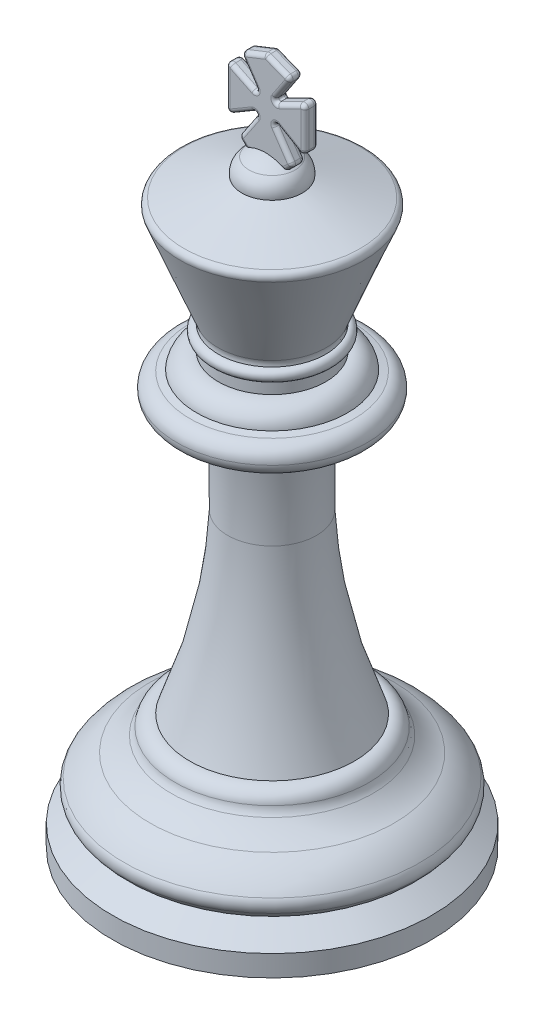
SolidWorks part; units mm, degrees
material "CA"
ref_plane "Front Plane" through (0, 0, 0) normal (0, 0, 1) x (1, 0, 0)
ref_plane "Top Plane" through (0, 0, 0) normal (0, 1, 0) x (1, 0, 0)
ref_plane "Right Plane" through (0, 0, 0) normal (1, 0, 0) x (0, 0, -1)
sketch "Sketch1" plane through (0, 0, 0) normal (0, 0, 1) x (1, 0, 0)
  line L0 (15.1895, 237.7707) -> (158.4441, 242.5229) construction
  line L1 (0, 0) -> (0, 46.3984)
  line L3 (-12.2343, 0) -> (0, 0)
  line L4 (-12.2343, 0) -> (-12.2343, 1.6147)
  line L5 (-12.2343, 1.6147) -> (-10.4135, 2.8152)
  line L6 (-6.3061, 29.5191) -> (-3.8024, 29.5191)
  line L7 (-6.3061, 31.6075) -> (-5.7756, 31.7201)
  line L8 (-4.1176, 32.9569) -> (-4.1176, 33.9091)
  line L9 (-4.157, 35.2434) -> (-7.0464, 42.4789)
  line L10 (-6.7515, 43.1108) -> (-2.313, 44.5702)
  arc A0 (-10.4135, 2.8152) -> (-11.3239, 3.6356) centre (-9.0682, 5.2235) cw
  arc A1 (-11.3239, 3.6356) -> (-11.3239, 4.656) centre (-10.5991, 4.1458) cw
  arc A2 (-11.3239, 4.656) -> (-9.353, 6.2967) centre (-7.2936, 1.8189) cw
  arc A3 (-9.353, 6.2967) -> (-7.7324, 7.4572) centre (-11.5541, 11.0825) ccw
  arc A4 (-7.7324, 7.4572) -> (-7.4365, 8.0365) centre (-8.5663, 8.2483) ccw
  arc A5 (-7.4365, 8.0365) -> (-6.3061, 8.8843) centre (-6.409, 7.844) cw
  arc A6 (-6.3061, 8.8843) -> (-3.399, 22.4026) centre (-45.4209, 24.3679) ccw
  arc A7 (-3.399, 22.4026) -> (-3.8024, 29.5191) centre (-43.5831, 23.6941) ccw
  arc A8 (-6.3061, 29.5191) -> (-7.2936, 30.5066) centre (-6.3061, 30.5066) cw
  arc A9 (-7.2936, 30.5066) -> (-6.3061, 31.6075) centre (-6.1863, 30.5066) cw
  arc A10 (-5.7756, 31.7201) -> (-4.1176, 32.9569) centre (-4.3282, 31.5095) cw
  arc A11 (-4.1176, 33.9091) -> (-4.1176, 34.7857) centre (-4.157, 34.3474) cw
  arc A12 (-4.1176, 34.7857) -> (-4.157, 35.2434) centre (-4.8927, 34.9496) ccw
  arc A13 (-7.0464, 42.4789) -> (-6.7515, 43.1108) centre (-6.6021, 42.6563) cw
  arc A14 (0, 46.3984) -> (-1.7625, 45.8266) centre (0, 43.396) ccw
  arc A15 (-1.7625, 45.8266) -> (-2.313, 44.5702) centre (-0.9666, 44.729) ccw
revolve "Revolve1" add sketch "Sketch1" angle 360 about L1
sketch "Sketch2" plane through (0, 0, 0) normal (0, 0, 1) x (1, 0, 0)
  line L0 (-1.5126, 45.8266) -> (-2.0841, 46.3982)
  line L1 (-2.0841, 46.3982) -> (-0.7379, 48.3914)
  line L3 (-0.9221, 48.5877) -> (-3.019, 47.3584)
  line L4 (-3.019, 47.3584) -> (-3.019, 51.0855)
  line L5 (-3.019, 51.0855) -> (-0.9128, 50.0595)
  line L6 (-0.7375, 50.2603) -> (-1.9619, 52.0937)
  line L7 (-1.9619, 52.0937) -> (0, 52.8709)
  line L8 (0, 52.8709) -> (0, 45.8266) construction
  line L9 (1.9619, 52.0937) -> (0, 52.8709)
  line L10 (0.7375, 50.2603) -> (1.9619, 52.0937)
  line L11 (3.019, 51.0855) -> (0.9128, 50.0595)
  line L12 (3.019, 47.3584) -> (3.019, 51.0855)
  line L13 (0.9221, 48.5877) -> (3.019, 47.3584)
  line L14 (2.0841, 46.3982) -> (0.7379, 48.3914)
  line L15 (1.5126, 45.8266) -> (2.0841, 46.3982)
  line L16 (1.7625, 45.8266) -> (-1.7625, 45.8266) construction
  line L17 (1.5126, 45.8266) -> (-1.5126, 45.8266)
  arc A0 (1.7625, 45.8266) -> (-1.7625, 45.8266) centre (0, 43.396) ccw
  arc A1 (1.6137, 45.9278) -> (-1.6137, 45.9278) centre (0, 43.396) ccw construction
  arc A2 (0, 46.3984) -> (-1.7625, 45.8266) centre (0, 43.396) ccw construction
  arc A4 (-0.7379, 48.3914) -> (-0.9221, 48.5877) centre (-0.8523, 48.4686) ccw
  arc A5 (-0.9128, 50.0595) -> (-0.7375, 50.2603) centre (-0.8523, 50.1836) ccw
  arc A6 (0.9128, 50.0595) -> (0.7375, 50.2603) centre (0.8523, 50.1836) cw
  arc A7 (0.7379, 48.3914) -> (0.9221, 48.5877) centre (0.8523, 48.4686) cw
extrude "Boss-Extrude1" add sketch "Sketch2" along normal mid plane 1.016 separate body
fillet "Fillet1" radius 0.3048
